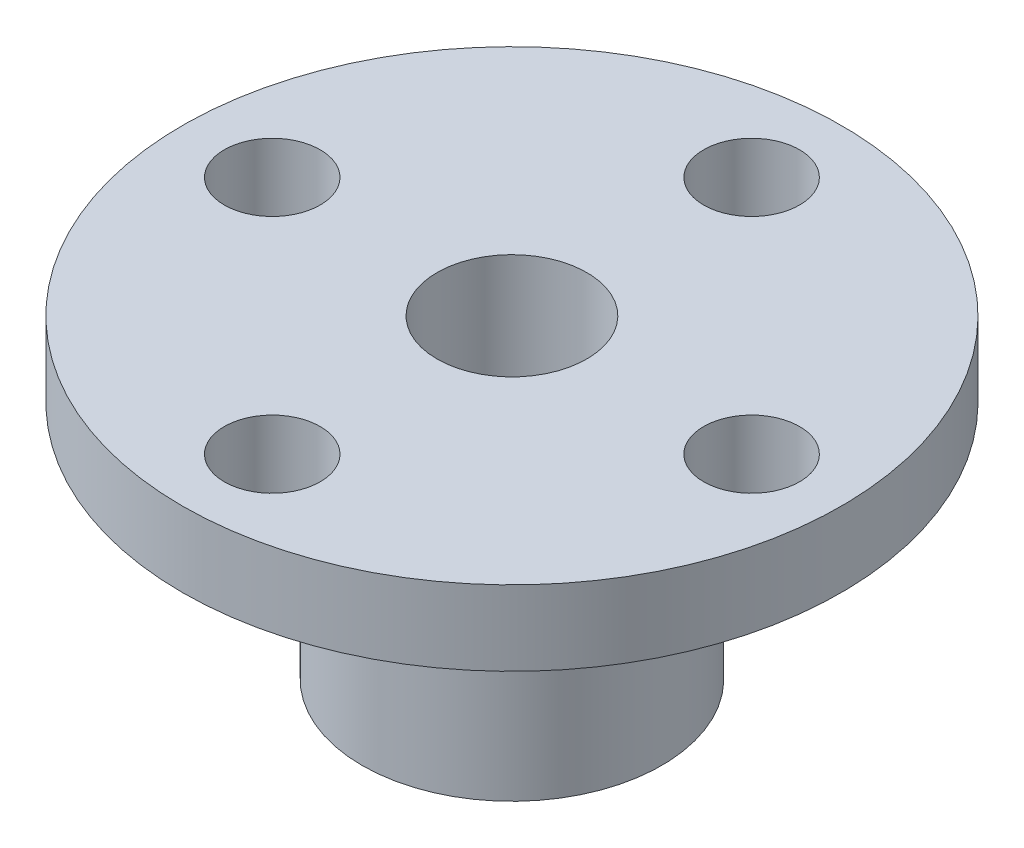
SolidWorks part; units mm, degrees
material "镀铬不锈钢"
ref_plane "前视基准面" through (0, 0, 0) normal (0, 0, 1) x (1, 0, 0)
ref_plane "上视基准面" through (0, 0, 0) normal (0, 1, 0) x (1, 0, 0)
ref_plane "右视基准面" through (0, 0, 0) normal (1, 0, 0) x (0, 0, -1)
sketch "草图1" plane through (0, 0, 0) normal (0, 1, 0) x (1, 0, 0)
  circle A0 centre (0, 0) radius 2.5
  circle A1 centre (0, 0) radius 5
  dimension "D1" = 5
  dimension "D2" = 10
extrude "凸台-拉伸1" add sketch "草图1" along normal blind 8
ref_plane "基准面1" through (0, 8, 0) normal (0, 1, 0) x (-1, 0, 0)
sketch "草图2" plane through (0, 8, 0) normal (0, 1, 0) x (-1, 0, 0)
  circle A0 centre (0, 0) radius 2.5
  circle A1 centre (0, 0) radius 11
  circle A2 centre (0, 0) radius 8 construction
  circle A3 centre (-8, 0) radius 1.6
  circle A4 centre (0, 8) radius 1.6
  circle A5 centre (8, 0) radius 1.6
  circle A6 centre (0, -8) radius 1.6
  point P16 (0, 0)
  dimension "D1" = 22
  dimension "D2" = 16
  dimension "D3" = 5
  dimension "D4" = 3.2
  dimension "D5" = 4
extrude "凸台-拉伸2" add sketch "草图2" along normal blind 2.5
